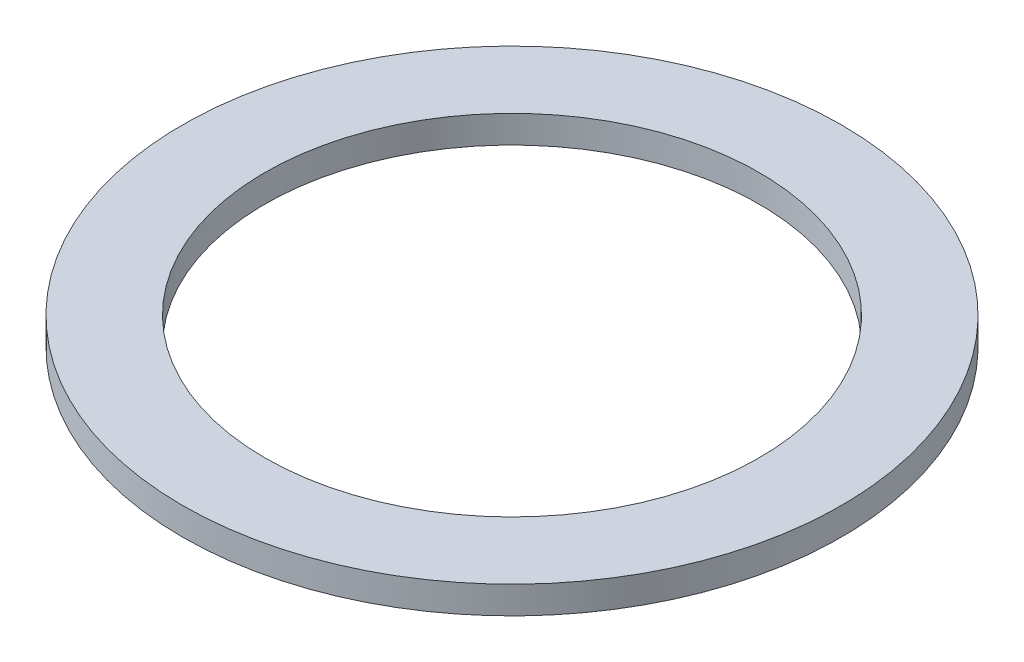
SolidWorks part; units mm, degrees
ref_plane "Plan de face" through (0, 0, 0) normal (0, 0, 1) x (1, 0, 0)
ref_plane "Plan de dessus" through (0, 0, 0) normal (0, 1, 0) x (1, 0, 0)
ref_plane "Plan de droite" through (0, 0, 0) normal (1, 0, 0) x (0, 0, -1)
sketch "Esquisse1" plane through (0, 0, 0) normal (0, 1, 0) x (1, 0, 0)
  circle A0 centre (0, 0) radius 18
  circle A1 centre (0, 0) radius 24
  dimension "D1" = 36
  dimension "D2" = 48
extrude "Boss.-Extru.1" add sketch "Esquisse1" along normal blind 2
